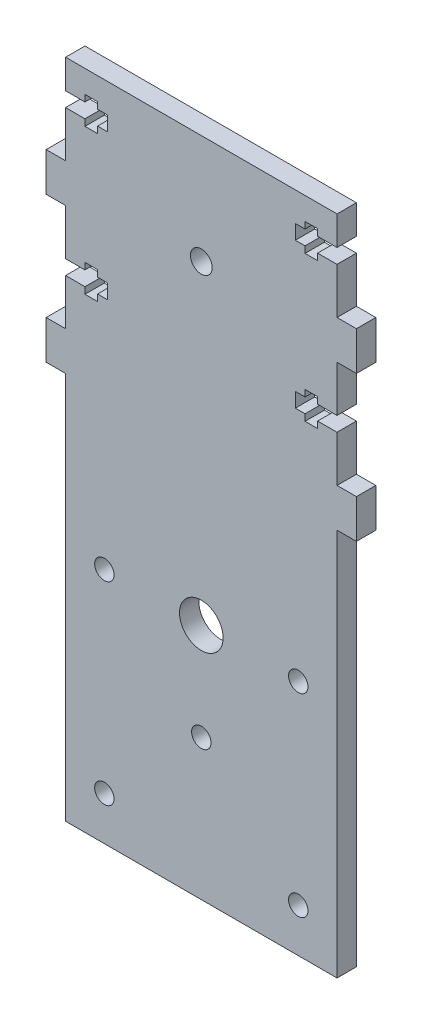
SolidWorks part; units mm, degrees
ref_plane "前视基准面" through (0, 0, 0) normal (0, 0, 1) x (1, 0, 0)
ref_plane "上视基准面" through (0, 0, 0) normal (0, 1, 0) x (1, 0, 0)
ref_plane "右视基准面" through (0, 0, 0) normal (1, 0, 0) x (0, 0, -1)
sketch "草图1" plane through (0, 0, 0) normal (0, 0, 1) x (1, 0, 0)
  line L1 (0, 4.863) -> (-4, 4.863)
  line L2 (-4, 4.863) -> (-4, 12.863)
  line L3 (-4, 12.863) -> (0, 12.863)
  line L5 (0, 22.363) -> (4, 22.363)
  line L6 (4, 22.363) -> (4, 21.013)
  line L7 (4, 21.013) -> (6.6, 21.013)
  line L8 (6.6, 21.013) -> (6.6, 22.363)
  line L9 (6.6, 22.363) -> (8.6, 22.363)
  line L10 (8.6, 22.363) -> (8.6, 25.363)
  line L11 (8.6, 25.363) -> (6.6, 25.363)
  line L12 (6.6, 25.363) -> (6.6, 26.713)
  line L13 (6.6, 26.713) -> (4, 26.713)
  line L14 (4, 26.713) -> (4, 25.363)
  line L15 (4, 25.363) -> (0, 25.363)
  line L16 (0, 25.363) -> (0, 31.363)
  line L17 (0, 31.363) -> (56, 31.363)
  line L18 (0, 25.363) -> (0, 22.363) construction
  line L20 (28, 31.363) -> (28, 28.363) construction
  line L21 (-4, -21.137) -> (0, -21.137) construction
  line L39 (-4, 8.863) -> (60, 8.863) construction
  line L40 (8.6, 23.863) -> (0, 23.863) construction
  line L51 (0, -7.637) -> (0, -4.637) construction
  line L52 (4, -7.637) -> (0, -7.637)
  line L53 (4, -8.987) -> (4, -7.637)
  line L54 (6.6, -8.987) -> (4, -8.987)
  line L55 (6.6, -7.637) -> (6.6, -8.987)
  line L56 (8.6, -7.637) -> (6.6, -7.637)
  line L57 (8.6, -4.637) -> (8.6, -7.637)
  line L58 (6.6, -4.637) -> (8.6, -4.637)
  line L59 (6.6, -3.287) -> (6.6, -4.637)
  line L60 (4, -3.287) -> (6.6, -3.287)
  line L61 (4, -4.637) -> (4, -3.287)
  line L62 (0, -4.637) -> (4, -4.637)
  line L63 (0, -4.637) -> (0, 4.863)
  line L65 (28, 8.863) -> (28, -56.137) construction
  line L83 (0, 22.363) -> (0, 12.863)
  line L84 (8.6, -6.137) -> (6.1425, -6.137) construction
  line L91 (-4, -25.137) -> (0, -25.137)
  line L92 (-4, -17.137) -> (-4, -25.137)
  line L93 (0, -17.137) -> (-4, -17.137)
  line L94 (0, -17.137) -> (0, -7.637)
  line L95 (28, -56.137) -> (8, -56.137) construction
  line L96 (28, -56.137) -> (28, -76.137) construction
  line L97 (56, 25.363) -> (56, 31.363)
  line L98 (49.4, 25.363) -> (49.4, 26.713)
  line L99 (49.4, 21.013) -> (49.4, 22.363)
  line L100 (52, 26.713) -> (52, 25.363)
  line L101 (52, 22.363) -> (52, 21.013)
  line L102 (52, 25.363) -> (56, 25.363)
  line L103 (49.4, 26.713) -> (52, 26.713)
  line L104 (47.4, 25.363) -> (49.4, 25.363)
  line L105 (47.4, 22.363) -> (47.4, 25.363)
  line L106 (49.4, 22.363) -> (47.4, 22.363)
  line L107 (52, 21.013) -> (49.4, 21.013)
  line L108 (56, 22.363) -> (52, 22.363)
  line L109 (56, 22.363) -> (56, 12.863)
  line L110 (60, 12.863) -> (56, 12.863)
  line L111 (47.4, -6.137) -> (49.8575, -6.137) construction
  line L112 (56, -7.637) -> (56, -4.637) construction
  line L113 (60, -21.137) -> (56, -21.137) construction
  line L114 (56, -17.137) -> (56, -7.637)
  line L115 (56, -17.137) -> (60, -17.137)
  line L116 (60, -17.137) -> (60, -25.137)
  line L117 (60, -25.137) -> (56, -25.137)
  line L118 (56, -4.637) -> (56, 4.863)
  line L119 (56, -4.637) -> (52, -4.637)
  line L120 (52, -4.637) -> (52, -3.287)
  line L121 (52, -3.287) -> (49.4, -3.287)
  line L122 (49.4, -3.287) -> (49.4, -4.637)
  line L123 (49.4, -4.637) -> (47.4, -4.637)
  line L124 (47.4, -4.637) -> (47.4, -7.637)
  line L125 (47.4, -7.637) -> (49.4, -7.637)
  line L126 (49.4, -7.637) -> (49.4, -8.987)
  line L127 (49.4, -8.987) -> (52, -8.987)
  line L128 (52, -8.987) -> (52, -7.637)
  line L129 (52, -7.637) -> (56, -7.637)
  line L130 (60, 4.863) -> (60, 12.863)
  line L131 (56, 4.863) -> (60, 4.863)
  line L133 (0, -25.137) -> (56, -25.137) construction
  line L134 (0, -25.137) -> (0, -105.137)
  line L135 (0, -105.137) -> (56, -105.137)
  line L136 (56, -25.137) -> (56, -105.137)
  circle A0 centre (28, 8.863) radius 2.25
  circle A16 centre (28, -56.137) radius 4.5
  circle A17 centre (8, -56.137) radius 2
  circle A22 centre (28, -76.137) radius 2
  circle A26 centre (48, -56.137) radius 2
  circle A27 centre (48, -96.137) radius 2
  circle A28 centre (8, -96.137) radius 2
  point P37 (28, -25.6947)
  dimension "D11" = 65
  dimension "D12" = 9
  dimension "D14" = 4
  dimension "D15" = 4
  dimension "D1" = 28
  dimension "D2" = 3
  dimension "D3" = 8
  dimension "D4" = 4
  dimension "D5" = 9.5
  dimension "D6" = 4
  dimension "D7" = 2
  dimension "D8" = 2.6
  dimension "D9" = 1.35
  dimension "D10" = 6
  dimension "D13" = 20
  dimension "D16" = 80
  dimension "D17" = 20
extrude "凸台-拉伸1" add sketch "草图1" along normal blind 4
sketch "草图3" plane through (0, 0, 0) normal (-1, 0, 0) x (0, 0, 1)
  line L0 (2, -7.637) -> (2, -4.637)
  line L1 (4, -7.637) -> (0, -7.637) construction
  line L2 (4, -4.637) -> (0, -4.637) construction
  circle A0 centre (2, -6.137) radius 1.5
